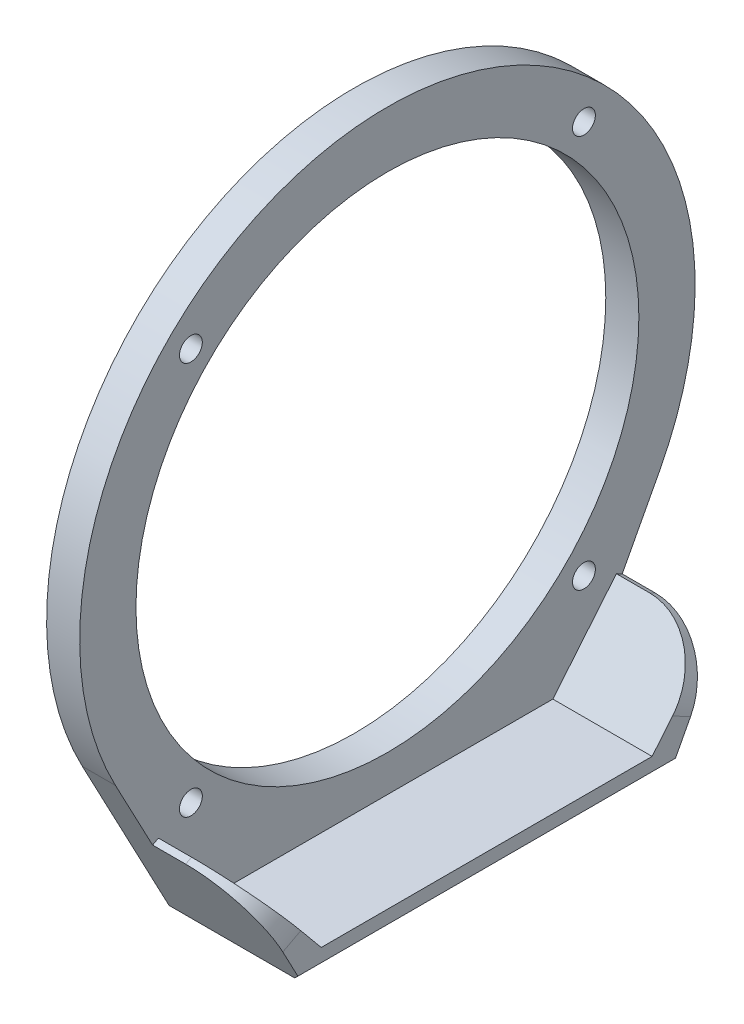
SolidWorks part; units mm, degrees
ref_plane "Front" through (0, 0, 0) normal (0, 0, 1) x (1, 0, 0)
ref_plane "Top" through (0, 0, 0) normal (0, 1, 0) x (1, 0, 0)
ref_plane "Right" through (0, 0, 0) normal (1, 0, 0) x (0, 0, -1)
sketch "Sketch1" plane through (0, 0, 0) normal (1, 0, 0) x (0, 0, -1)
  line L0 (-28, -46.5) -> (28, -46.5)
  line L1 (28, -46.5) -> (41.0983, -21.7526)
  line L2 (-28, -46.5) -> (-41.0983, -21.7526)
  circle A0 centre (0, 0) radius 38
  arc A1 (41.0983, -21.7526) -> (-41.0983, -21.7526) centre (0, 0) ccw
  point P6 (0, -46.5)
  dimension "D1" = 76
  dimension "D2" = 93
  dimension "D3" = 56
extrude "Boss-Extrude1" add sketch "Sketch1" along normal blind 5
sketch "Sketch2" plane through (5, 0, 0) normal (1, 0, 0) x (0, 0, -1)
  line L0 (-28, -46.5) -> (28, -46.5)
  line L1 (28, -46.5) -> (35.4848, -32.3586)
  line L2 (28, -46.5) -> (41.0983, -21.7526) construction
  line L3 (25, -43.5) -> (-25, -43.5)
  line L4 (-41.0983, -21.7526) -> (-28, -46.5) construction
  line L5 (-35.4848, -32.3586) -> (-28, -46.5)
  line L6 (-35.4848, -32.3586) -> (-34.6009, -31.8908)
  line L7 (-34.6009, -31.8908) -> (-25, -43.5)
  line L8 (35.4848, -32.3586) -> (34.6009, -31.8908)
  line L9 (34.6009, -31.8908) -> (25, -43.5)
  point P18 (0, -43.5)
  point P19 (0, -46.5)
  dimension "D1" = 3
  dimension "D2" = 16
  dimension "D3" = 1
  dimension "D4" = 3
extrude "Boss-Extrude2" add sketch "Sketch2" along normal blind 15
hole_wizard "#4 Clearance Hole1" positions "Sketch3" profile "Sketch4" hole size "#4" standard "ANSI Inch" end condition through all
sketch "Sketch3" plane through (0, 0, 0) normal (-1, 0, 0) x (0, 0, 1)
  line L0 (-29.6985, -29.6985) -> (29.6985, 29.6985) construction
  line L1 (29.6985, -29.6985) -> (-29.6985, 29.6985) construction
  point P0 (-29.6985, -29.6985)
  point P2 (-29.6985, 29.6985)
  point P4 (29.6985, 29.6985)
  point P6 (29.6985, -29.6985)
  point P14 (0, 0)
  point P16 (0, 0)
  dimension "D1" = 84
sketch "Sketch4" plane through (0, -29.6985, -29.6985) normal (0, 1, 0) x (0, 0, 1)
  line L0 (0, 0) -> (0, 20)
  line L1 (0, 20) -> (1.7272, 20)
  line L2 (1.7272, 20) -> (1.7272, 0)
  line L5 (1.7272, 0) -> (0, 0)
  line L11 (0, -6.35) -> (0, 107.95) construction
  dimension "Thru Hole Dia." = 3.4544
  dimension "Thru Hole Depth" = 20
fillet "Fillet1" radius 10 2 edges at (20, -32.1247, -35.0429) (20, -32.1247, 35.0429)
chamfer "Chamfer1" distance 1 angle 45 1 edges at (20, -46.5, 0)
